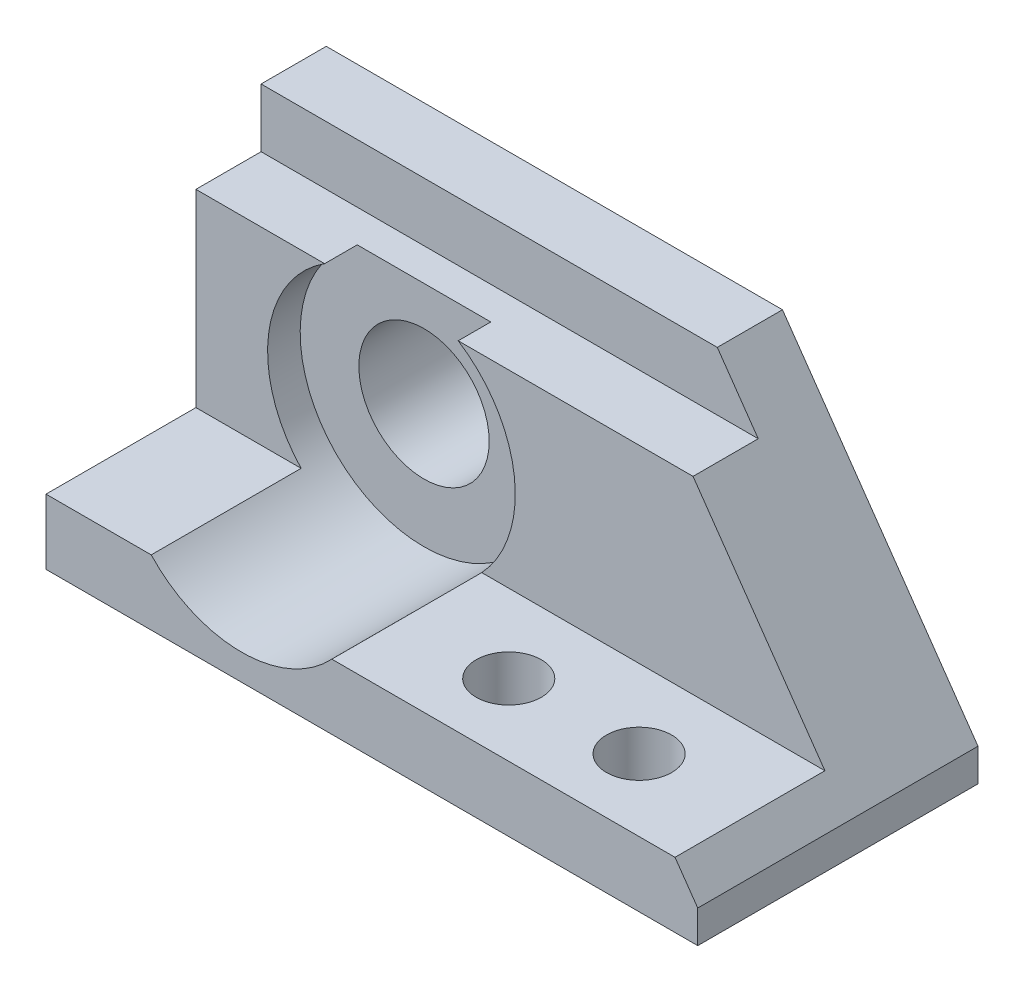
SolidWorks part; units mm, degrees
ref_plane "Piano frontale" through (0, 0, 0) normal (0, 0, 1) x (1, 0, 0)
ref_plane "Piano superiore" through (0, 0, 0) normal (0, 1, 0) x (1, 0, 0)
ref_plane "Piano destro" through (0, 0, 0) normal (1, 0, 0) x (0, 0, -1)
sketch "Schizzo1" plane through (0, 0, 0) normal (1, 0, 0) x (0, 0, -1)
  line L0 (0, 48) -> (0, 0)
  line L1 (0, 55) -> (0, -55) construction
  line L2 (0, 0) -> (-43, 0)
  line L3 (55, 0) -> (-55, 0) construction
  line L4 (-43, 0) -> (-43, 10)
  line L5 (-43, 10) -> (-20, 10)
  line L6 (-20, 10) -> (-20, 39)
  line L7 (-20, 39) -> (-10, 39)
  line L8 (-10, 39) -> (-10, 48)
  line L9 (-10, 48) -> (0, 48)
  dimension "D1" = 43
  dimension "D2" = 48
  dimension "D3" = 20
  dimension "D4" = 10
  dimension "D5" = 10
  dimension "D6" = 9
extrude "Estrusione-Estrusione1" add sketch "Schizzo1" along normal blind 100
sketch "Schizzo2" plane through (0, 0, 0) normal (0, 0, 1) x (1, 0, 0)
  line L0 (70, 48) -> (100, 5)
  line L1 (100, 48) -> (0, 48) construction
  line L2 (100, 39) -> (100, 10) construction
  line L3 (0, -23.65) -> (0, 23.65) construction
  line L4 (23.65, 0) -> (-23.65, 0) construction
  dimension "D1" = 70
  dimension "D2" = 5
extrude "Taglio-Estrusione1" cut sketch "Schizzo2" against normal through all and the other way through all
sketch "Schizzo3" plane through (0, 0, 43) normal (0, 0, 1) x (1, 0, 0)
  line L0 (23.65, 0) -> (-23.65, 0) construction
  line L1 (0, -23.65) -> (0, 23.65) construction
  circle A0 centre (30, 23) radius 19
  dimension "D1" = 38
  dimension "D2" = 23
  dimension "D3" = 30
extrude "Taglio-Estrusione2" cut sketch "Schizzo3" along normal through all and the other way blind 5 from surface at -23 starting at face at (43.1977, 24.5, 20)
hole_wizard "Foro Ø20.0 (20)-1" positions "Schizzo4" profile "Schizzo5" hole size "Ø20.0" standard "ISO" end condition through all
sketch "Schizzo4" plane through (0, 0, 15) normal (0, 0, 1) x (1, 0, 0)
  point P0 (30, 23)
sketch "Schizzo5" plane through (30, 23, 15) normal (1, 0, 0) x (0, -1, 0)
  line L0 (0, 0) -> (0, 15)
  line L1 (0, 15) -> (10, 15)
  line L2 (10, 15) -> (10, 0)
  line L5 (10, 0) -> (0, 0)
  line L11 (0, -6.35) -> (0, 107.95) construction
  dimension "Thru Hole Dia." = 20
  dimension "Thru Hole Depth" = 15
hole_wizard "Foro Ø10.0 (10)-1" positions "Schizzo6" profile "Schizzo7" hole size "Ø10.0" standard "ISO" end condition through all
sketch "Schizzo6" plane through (0, 10, 0) normal (0, 1, 0) x (1, 0, 0)
  line L1 (100, -43) -> (100, 0) construction
  line L2 (96.5116, -43) -> (43.8564, -43) construction
  point P0 (80, -32)
  point P2 (60, -32)
  point P7 (0, 0)
  point P8 (0, 0)
  dimension "D1" = 20
  dimension "D2" = 20
  dimension "D3" = 11
sketch "Schizzo7" plane through (80, 10, 32) normal (1, 0, 0) x (0, 0, 1)
  line L0 (0, 0) -> (0, 10)
  line L1 (0, 10) -> (5, 10)
  line L2 (5, 10) -> (5, 0)
  line L5 (5, 0) -> (0, 0)
  line L11 (0, -6.35) -> (0, 107.95) construction
  dimension "Thru Hole Dia." = 10
  dimension "Thru Hole Depth" = 10
